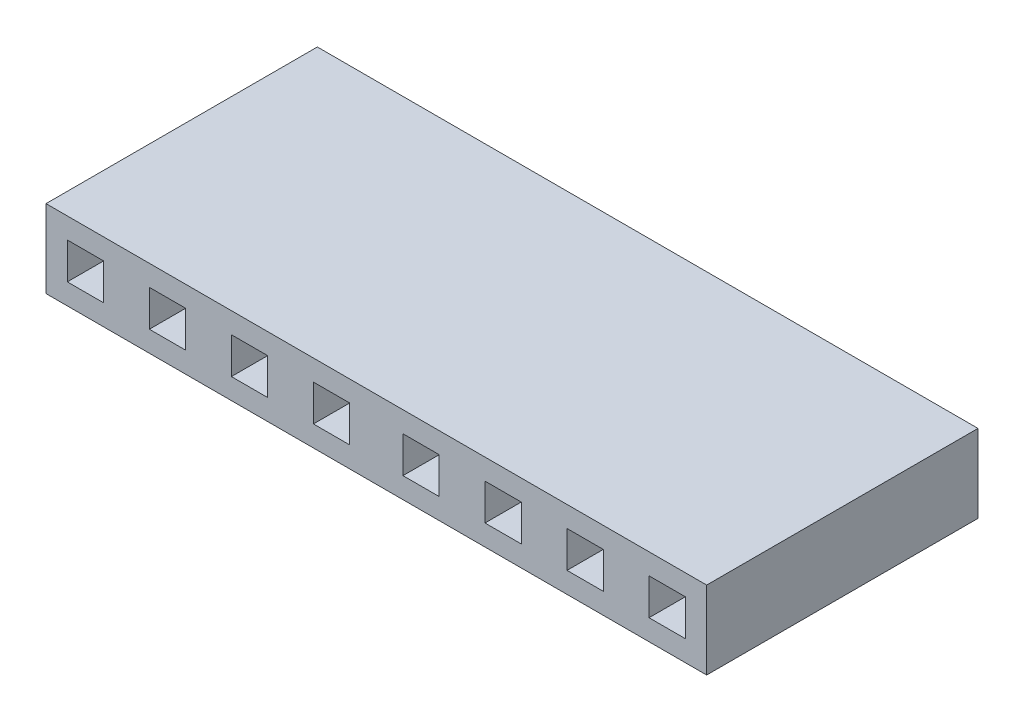
SolidWorks part; units mm, degrees
ref_plane "Alzado" through (0, 0, 0) normal (0, 0, 1) x (1, 0, 0)
ref_plane "Planta" through (0, 0, 0) normal (0, 1, 0) x (1, 0, 0)
ref_plane "Vista lateral" through (0, 0, 0) normal (1, 0, 0) x (0, 0, -1)
sketch "Croquis1" plane through (0, 0, 0) normal (0, 0, 1) x (1, 0, 0)
  line L1 (0, 0) -> (-20.94, 0)
  line L2 (0, 0) -> (0, 2.47)
  line L3 (0, 2.47) -> (-20.94, 2.47)
  line L4 (-20.94, 0) -> (-20.94, 2.47)
extrude "Saliente-Extruir1" add sketch "Croquis1" along normal blind 8.6
sketch "Croquis2" plane through (0, 0, 8.6) normal (0, 0, 1) x (1, 0, 0)
  line L3 (-15.0639, 0.66) -> (-13.9139, 0.66)
  line L4 (-13.9139, 1.81) -> (-13.9139, 0.66)
  line L5 (-15.0639, 1.81) -> (-13.9139, 1.81)
  line L6 (-12.4639, 1.81) -> (-11.3139, 1.81)
  line L7 (-12.4639, 1.81) -> (-12.4639, 0.66)
  line L8 (-12.4639, 0.66) -> (-11.3139, 0.66)
  line L9 (-11.3139, 1.81) -> (-11.3139, 0.66)
  line L10 (-15.0639, 1.81) -> (-15.0639, 0.66)
  line L11 (-17.6639, 0.66) -> (-16.5139, 0.66)
  line L12 (-16.5139, 1.81) -> (-16.5139, 0.66)
  line L13 (-17.6639, 1.81) -> (-16.5139, 1.81)
  line L14 (-17.6639, 1.81) -> (-17.6639, 0.66)
  line L15 (-20.2639, 0.66) -> (-19.1139, 0.66)
  line L16 (-19.1139, 1.81) -> (-19.1139, 0.66)
  line L17 (-20.2639, 1.81) -> (-19.1139, 1.81)
  line L18 (-20.2639, 1.81) -> (-20.2639, 0.66)
  line L19 (-0.6761, 1.81) -> (-0.6761, 0.66)
  line L20 (-0.6761, 1.81) -> (-1.8261, 1.81)
  line L21 (-1.8261, 1.81) -> (-1.8261, 0.66)
  line L22 (-0.6761, 0.66) -> (-1.8261, 0.66)
  line L23 (-3.2761, 1.81) -> (-3.2761, 0.66)
  line L24 (-3.2761, 1.81) -> (-4.4261, 1.81)
  line L25 (-4.4261, 1.81) -> (-4.4261, 0.66)
  line L26 (-3.2761, 0.66) -> (-4.4261, 0.66)
  line L27 (-5.8761, 1.81) -> (-5.8761, 0.66)
  line L28 (-9.6261, 1.81) -> (-9.6261, 0.66)
  line L29 (-8.4761, 0.66) -> (-9.6261, 0.66)
  line L30 (-8.4761, 1.81) -> (-8.4761, 0.66)
  line L31 (-8.4761, 1.81) -> (-9.6261, 1.81)
  line L32 (-5.8761, 1.81) -> (-7.0261, 1.81)
  line L33 (-7.0261, 1.81) -> (-7.0261, 0.66)
  line L34 (-5.8761, 0.66) -> (-7.0261, 0.66)
  dimension "D1" = 4
extrude "Cortar-Extruir1" cut sketch "Croquis2" against normal blind 6.45
